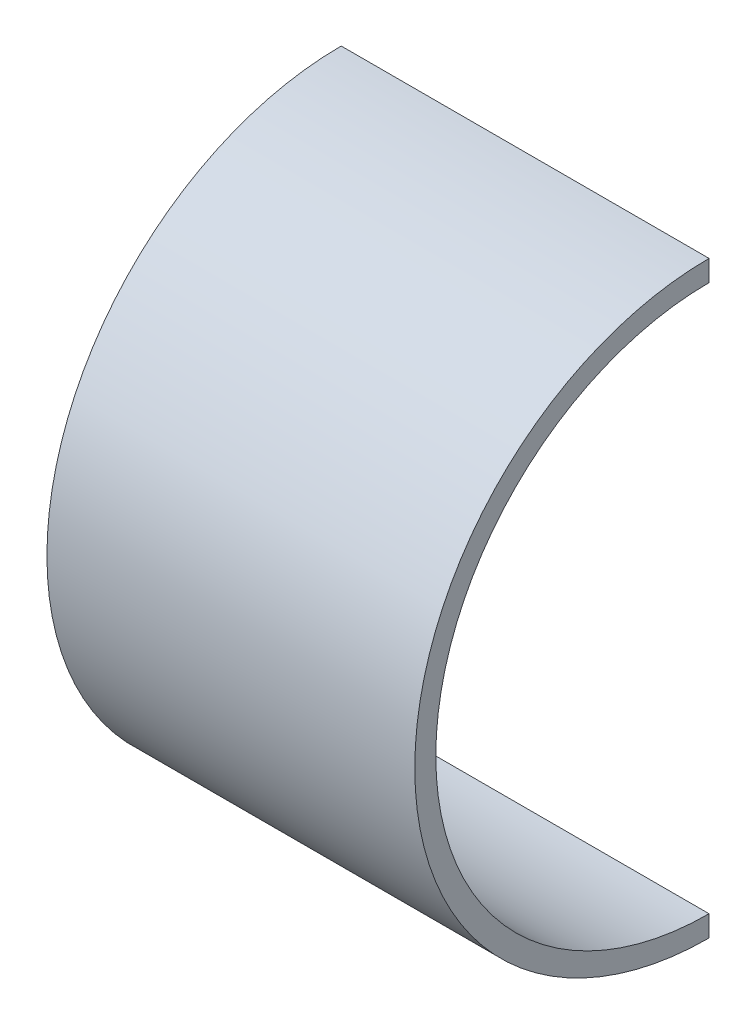
SolidWorks part; units mm, degrees
ref_plane "Front Plane" through (0, 0, 0) normal (0, 0, 1) x (1, 0, 0)
ref_plane "Top Plane" through (0, 0, 0) normal (0, 1, 0) x (1, 0, 0)
ref_plane "Right Plane" through (0, 0, 0) normal (1, 0, 0) x (0, 0, -1)
sketch "Sketch1" plane through (0, 0, 0) normal (1, 0, 0) x (0, 0, -1)
  line L0 (0, 711.2) -> (0, 660.4)
  line L1 (0, -660.4) -> (0, -711.2)
  arc A0 (0, 660.4) -> (0, -660.4) centre (0, 0) ccw
  arc A1 (0, 711.2) -> (0, -711.2) centre (0, 0) ccw
extrude "Boss-Extrude1" add sketch "Sketch1" along normal blind 889
